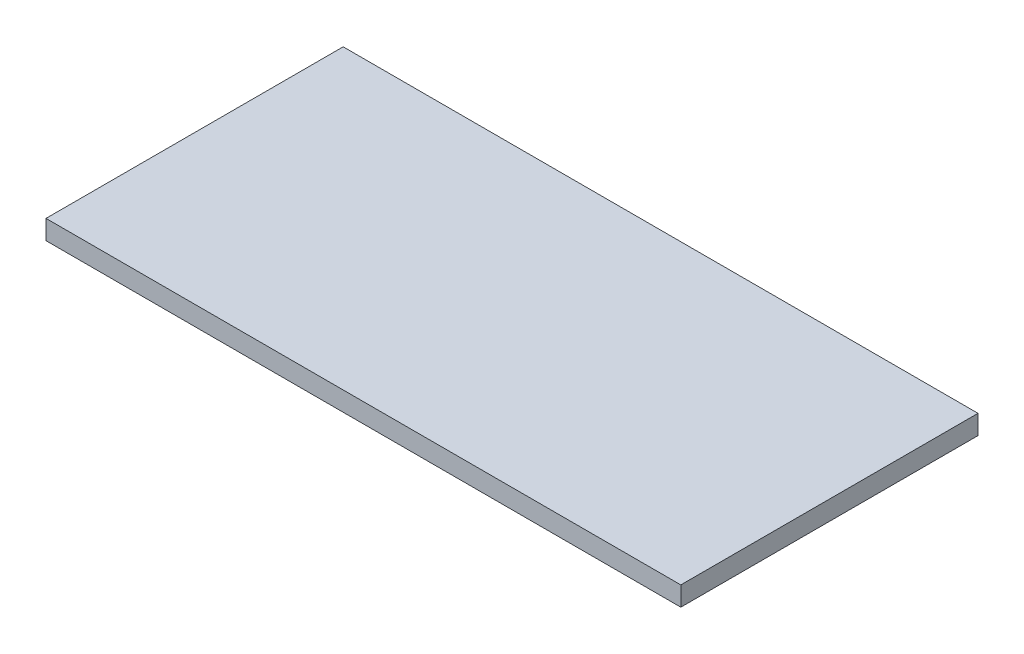
SolidWorks part; units mm, degrees
ref_plane "Front Plane" through (0, 0, 0) normal (0, 0, 1) x (1, 0, 0)
ref_plane "Top Plane" through (0, 0, 0) normal (0, 1, 0) x (1, 0, 0)
ref_plane "Right Plane" through (0, 0, 0) normal (1, 0, 0) x (0, 0, -1)
sketch "Sketch1" plane through (0, 0, 0) normal (0, 1, 0) x (1, 0, 0)
  line L1 (-164.2182, 76.878) -> (164.2182, 76.878)
  line L2 (-164.2182, 76.878) -> (-164.2182, -76.878)
  line L3 (-164.2182, -76.878) -> (164.2182, -76.878)
  line L4 (164.2182, 76.878) -> (164.2182, -76.878)
  line L5 (-164.2182, 76.878) -> (164.2182, -76.878) construction
  line L6 (-164.2182, -76.878) -> (164.2182, 76.878) construction
  point P0 (0, 0)
extrude "Boss-Extrude1" add sketch "Sketch1" along normal blind 10
